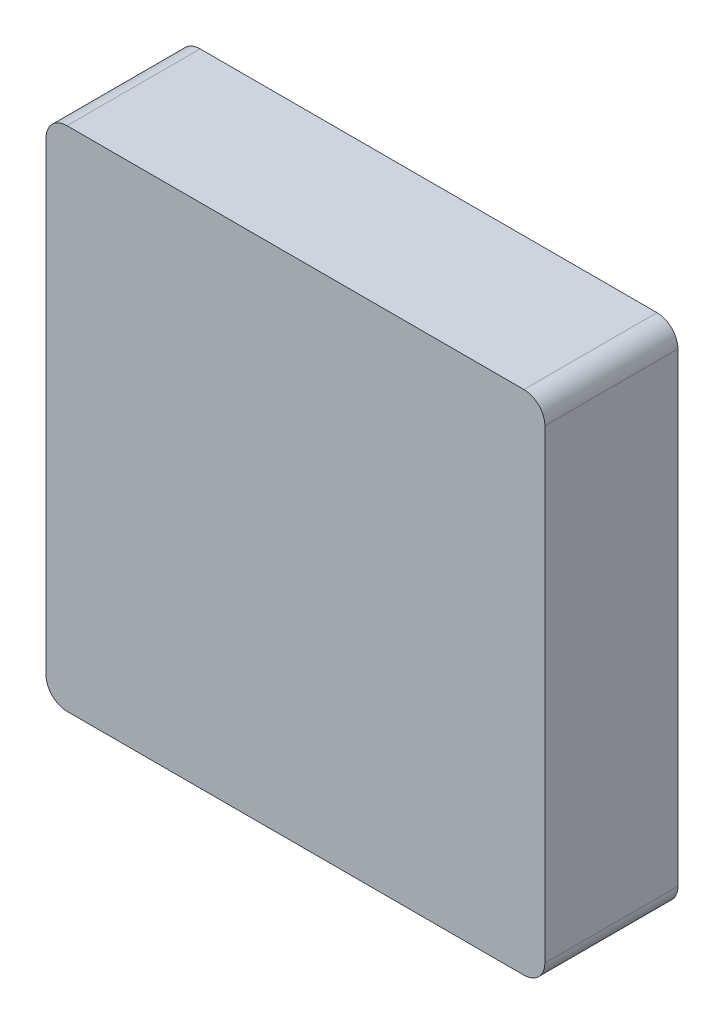
SolidWorks part; units mm, degrees
material "AISI 1045 Steel, cold drawn"
ref_plane "Front Plane" through (0, 0, 0) normal (0, 0, 1) x (1, 0, 0)
ref_plane "Top Plane" through (0, 0, 0) normal (0, 1, 0) x (1, 0, 0)
ref_plane "Right Plane" through (0, 0, 0) normal (1, 0, 0) x (0, 0, -1)
sketch "Sketch1" plane through (0, 0, 0) normal (0, 0, 1) x (1, 0, 0)
  line L1 (5.95, -6.05) -> (-5.95, -6.05)
  line L2 (5.95, -6.05) -> (5.95, 6.05)
  line L3 (5.95, 6.05) -> (-5.95, 6.05)
  line L4 (-5.95, -6.05) -> (-5.95, 6.05)
  line L5 (5.95, -6.05) -> (-5.95, 6.05) construction
  line L6 (5.95, 6.05) -> (-5.95, -6.05) construction
  point P0 (0, 0)
  dimension "D1" = 11.9
  dimension "D2" = 12.1
extrude "Boss-Extrude1" add sketch "Sketch1" along normal blind 3.175
fillet "Fillet1" radius 0.5 4 edges at (5.95, 6.05, 1.5875) (5.95, -6.05, 1.5875) (-5.95, -6.05, 1.5875) (-5.95, 6.05, 1.5875)
